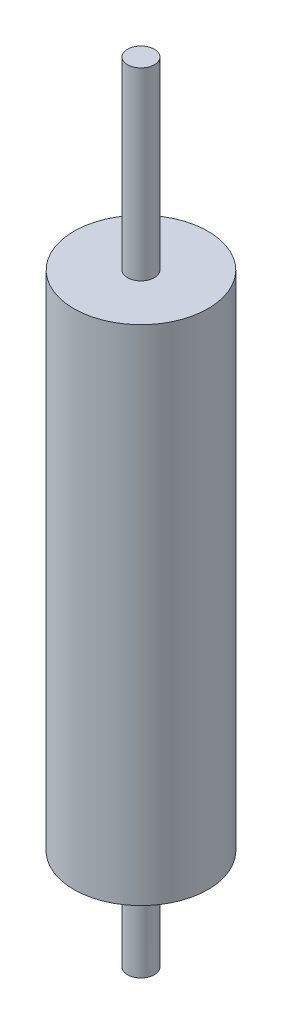
SolidWorks part; units mm, degrees
ref_plane "Front Plane" through (0, 0, 0) normal (0, 0, 1) x (1, 0, 0)
ref_plane "Top Plane" through (0, 0, 0) normal (0, 1, 0) x (1, 0, 0)
ref_plane "Right Plane" through (0, 0, 0) normal (1, 0, 0) x (0, 0, -1)
sketch "Sketch1" plane through (0, 0, 0) normal (0, 1, 0) x (1, 0, 0)
  circle A0 centre (0, 0) radius 20
  dimension "D1" = 40
extrude "Boss-Extrude1" add sketch "Sketch1" along normal blind 150
sketch "Sketch2" plane through (0, 0, 0) normal (0, -1, 0) x (1, 0, 0)
  circle A0 centre (0, 0) radius 4
  dimension "D1" = 8
extrude "Boss-Extrude2" add sketch "Sketch2" along normal blind 30
ref_plane "Plane1" through (0, 75, 0) normal (0, -1, 0) x (-1, 0, 0)
mirror "Mirror1" about plane through (0, 75, 0) normal (0, -1, 0) of "Boss-Extrude2"
sketch "Sketch3" plane through (0, -30, 0) normal (0, -1, 0) x (1, 0, 0)
  circle A0 centre (0, 0) radius 4
extrude "Boss-Extrude3" add sketch "Sketch3" against normal blind 25 from surface at -210 starting at face at (0, 180, -4)
